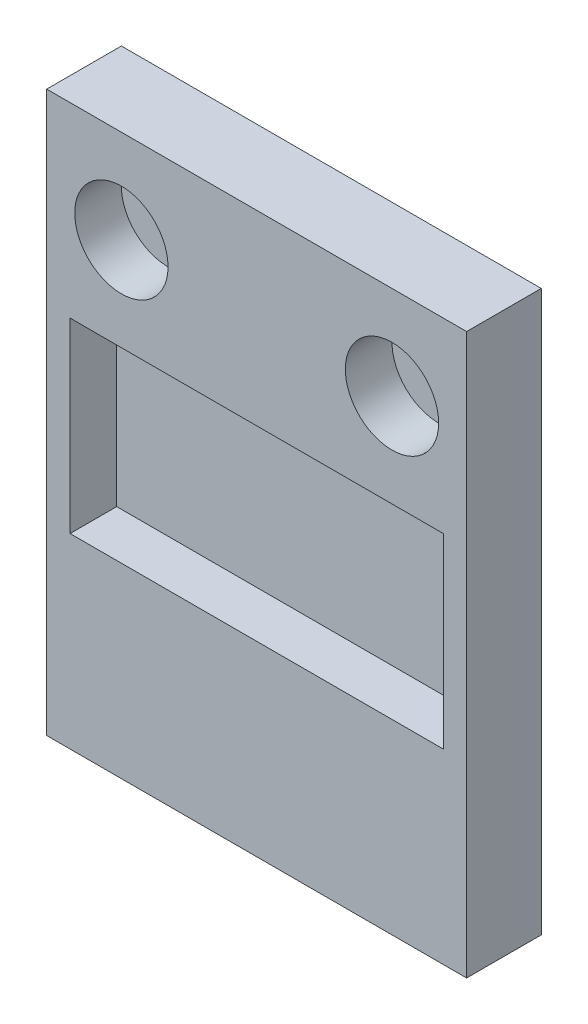
SolidWorks part; units mm, degrees
ref_plane "Front Plane" through (0, 0, 0) normal (0, 0, 1) x (1, 0, 0)
ref_plane "Top Plane" through (0, 0, 0) normal (0, 1, 0) x (1, 0, 0)
ref_plane "Right Plane" through (0, 0, 0) normal (1, 0, 0) x (0, 0, -1)
sketch "Sketch1" plane through (0, 0, 0) normal (0, 0, 1) x (1, 0, 0)
  line L1 (-22.5, 30) -> (22.5, 30)
  line L2 (-22.5, 30) -> (-22.5, -30)
  line L3 (-22.5, -30) -> (22.5, -30)
  line L4 (22.5, 30) -> (22.5, -30)
  line L5 (-22.5, 30) -> (22.5, -30) construction
  line L6 (-22.5, -30) -> (22.5, 30) construction
  point P0 (0, 0)
  dimension "D1" = 60
  dimension "D2" = 45
extrude "Boss-Extrude1" add sketch "Sketch1" along normal blind 8
sketch "Sketch2" plane through (0, 0, 8) normal (0, 0, 1) x (1, 0, 0)
  line L0 (-22.5, 20) -> (22.5, 20) construction
  line L1 (-22.5, 30) -> (-22.5, -30) construction
  line L2 (22.5, -30) -> (22.5, 30) construction
  line L3 (-22.5, 10) -> (22.5, 10) construction
  line L5 (-20, 10) -> (20, 10)
  line L6 (-20, 10) -> (-20, -10)
  line L7 (-20, -10) -> (20, -10)
  line L8 (20, 10) -> (20, -10)
  circle A0 centre (-14.5, 20) radius 5
  circle A1 centre (14.5, 20) radius 5
  dimension "D4" = 10
  dimension "D1" = 10
  dimension "D2" = 8
  dimension "D3" = 8
  dimension "D5" = 20
  dimension "D6" = 2.5
  dimension "D7" = 40
  dimension "D8" = 20
extrude "Cut-Extrude1" cut sketch "Sketch2" against normal blind 5
